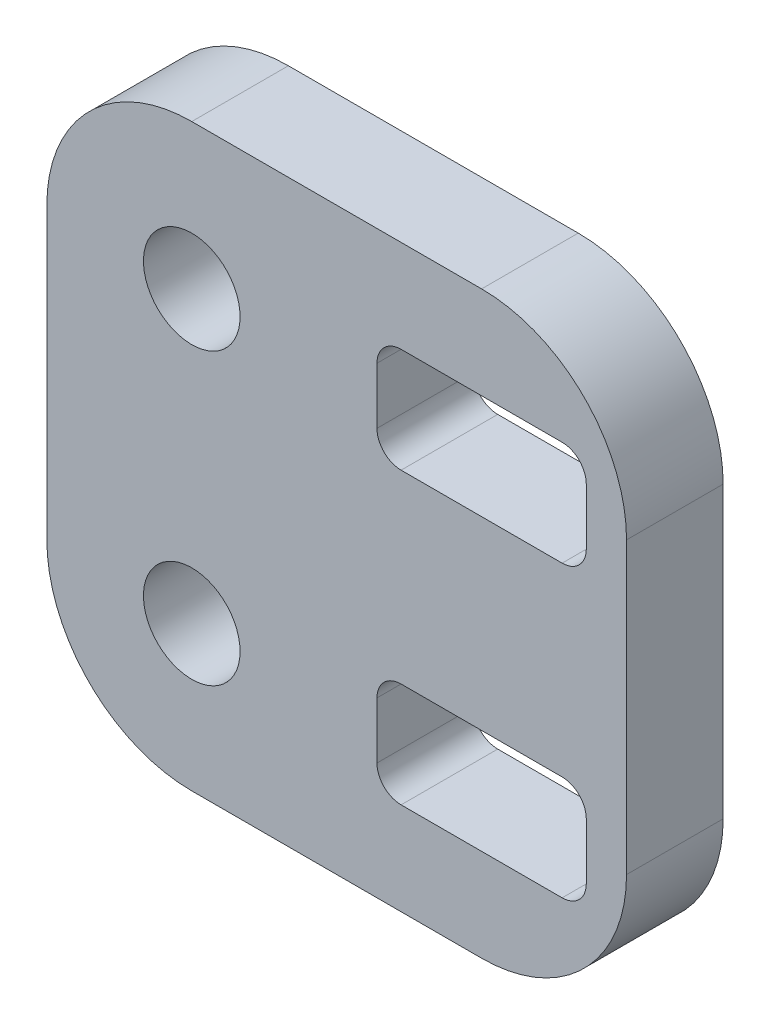
SolidWorks part; units mm, degrees
ref_plane "Alzado" through (0, 0, 0) normal (0, 0, 1) x (1, 0, 0)
ref_plane "Planta" through (0, 0, 0) normal (0, 1, 0) x (1, 0, 0)
ref_plane "Vista lateral" through (0, 0, 0) normal (1, 0, 0) x (0, 0, -1)
sketch "Model" plane through (0, 0, 0) normal (0, 0, 1) x (1, 0, 0)
  line L0 (195.3359, 161.3332) -> (204.3359, 161.3332)
  line L1 (208.8359, 165.8332) -> (208.8359, 174.8332)
  line L2 (204.3359, 179.3332) -> (195.3359, 179.3332)
  line L3 (190.8359, 174.8332) -> (190.8359, 165.8332)
  line L4 (206.8359, 173.2082) -> (201.8359, 173.2082)
  line L5 (201.0859, 173.9582) -> (201.0859, 175.7082)
  line L6 (201.8359, 176.4582) -> (206.8359, 176.4582)
  line L7 (207.5859, 175.7082) -> (207.5859, 173.9582)
  line L8 (206.8359, 164.2082) -> (201.8359, 164.2082)
  line L9 (201.0859, 164.9582) -> (201.0859, 166.7082)
  line L10 (201.8359, 167.4582) -> (206.8359, 167.4582)
  line L11 (207.5859, 166.7082) -> (207.5859, 164.9582)
  circle A0 centre (195.3359, 174.8332) radius 1.5
  circle A1 centre (195.3359, 165.8332) radius 1.5
  arc A2 (204.3359, 161.3332) -> (208.8359, 165.8332) centre (204.3359, 165.8332) ccw
  arc A3 (208.8359, 174.8332) -> (204.3359, 179.3332) centre (204.3359, 174.8332) ccw
  arc A4 (195.3359, 179.3332) -> (190.8359, 174.8332) centre (195.3359, 174.8332) ccw
  arc A5 (190.8359, 165.8332) -> (195.3359, 161.3332) centre (195.3359, 165.8332) ccw
  arc A6 (201.0859, 173.9582) -> (201.8359, 173.2082) centre (201.8359, 173.9582) ccw
  arc A7 (201.8359, 176.4582) -> (201.0859, 175.7082) centre (201.8359, 175.7082) ccw
  arc A8 (207.5859, 175.7082) -> (206.8359, 176.4582) centre (206.8359, 175.7082) ccw
  arc A9 (206.8359, 173.2082) -> (207.5859, 173.9582) centre (206.8359, 173.9582) ccw
  arc A10 (201.0859, 164.9582) -> (201.8359, 164.2082) centre (201.8359, 164.9582) ccw
  arc A11 (201.8359, 167.4582) -> (201.0859, 166.7082) centre (201.8359, 166.7082) ccw
  arc A12 (207.5859, 166.7082) -> (206.8359, 167.4582) centre (206.8359, 166.7082) ccw
  arc A13 (206.8359, 164.2082) -> (207.5859, 164.9582) centre (206.8359, 164.9582) ccw
extrude "Saliente-Extruir1" add sketch "Model" along normal blind 3
